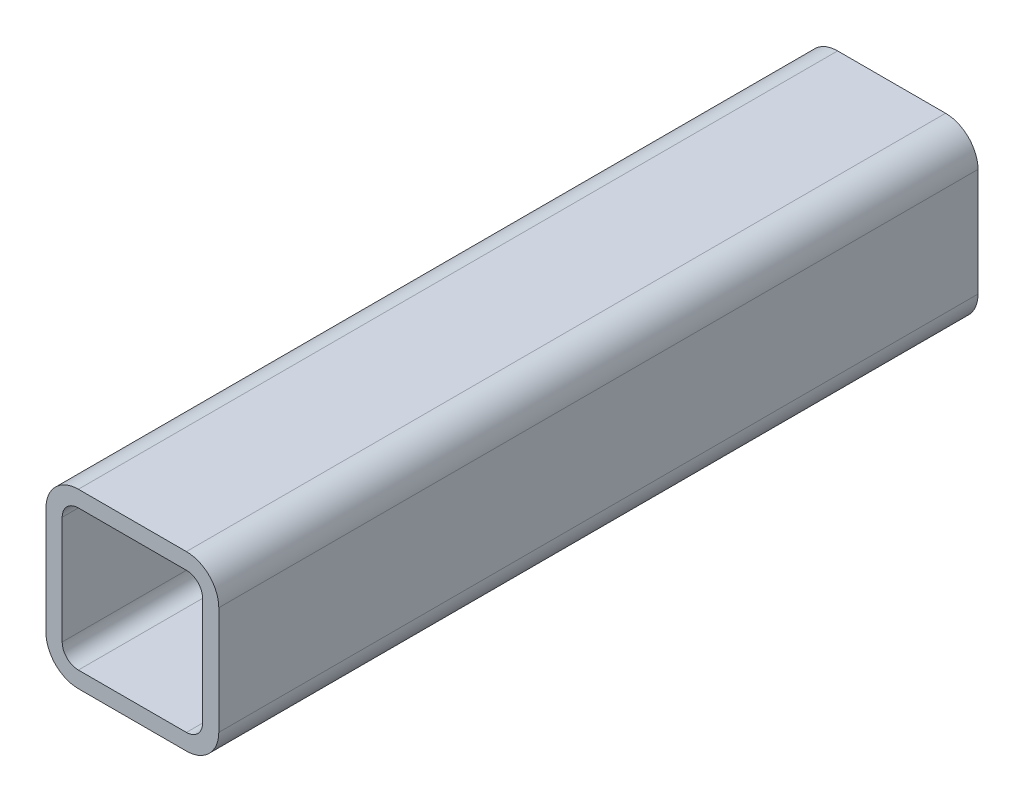
SolidWorks part; units mm, degrees
ref_plane "Płaszczyzna przednia" through (0, 0, 0) normal (0, 0, 1) x (1, 0, 0)
ref_plane "Płaszczyzna górna" through (0, 0, 0) normal (0, 1, 0) x (1, 0, 0)
ref_plane "Płaszczyzna prawa" through (0, 0, 0) normal (1, 0, 0) x (0, 0, -1)
sketch "Szkic1" plane through (0, 0, 0) normal (0, 0, 1) x (1, 0, 0)
  line L1 (9.53, 0) -> (41.27, 0)
  line L2 (0, 9.53) -> (0, 41.27)
  line L3 (9.53, 50.8) -> (41.27, 50.8)
  line L4 (50.8, 9.53) -> (50.8, 41.27)
  line L5 (9.52, 46.04) -> (41.28, 46.04)
  line L6 (4.76, 41.28) -> (4.76, 9.52)
  line L7 (9.52, 4.76) -> (41.28, 4.76)
  line L8 (46.04, 41.28) -> (46.04, 9.52)
  arc A0 (4.76, 9.52) -> (9.52, 4.76) centre (9.52, 9.52) ccw
  arc A1 (41.28, 4.76) -> (46.04, 9.52) centre (41.28, 9.52) ccw
  arc A2 (46.04, 41.28) -> (41.28, 46.04) centre (41.28, 41.28) ccw
  arc A3 (4.76, 41.28) -> (9.52, 46.04) centre (9.52, 41.28) cw
  arc A4 (41.27, 50.8) -> (50.8, 41.27) centre (41.27, 41.27) cw
  arc A5 (50.8, 9.53) -> (41.27, 0) centre (41.27, 9.53) cw
  arc A6 (9.53, 0) -> (0, 9.53) centre (9.53, 9.53) cw
  arc A7 (0, 41.27) -> (9.53, 50.8) centre (9.53, 41.27) cw
  dimension "D7" = 4.76
  dimension "D8" = 9.53
  dimension "D1" = 50.8
  dimension "D2" = 50.8
  dimension "D3" = 41.28
  dimension "D4" = 41.28
  dimension "D5" = 4.76
  dimension "D6" = 4.76
extrude "Dodanie-wyciągnięcie1" add sketch "Szkic1" along normal blind 223.2
